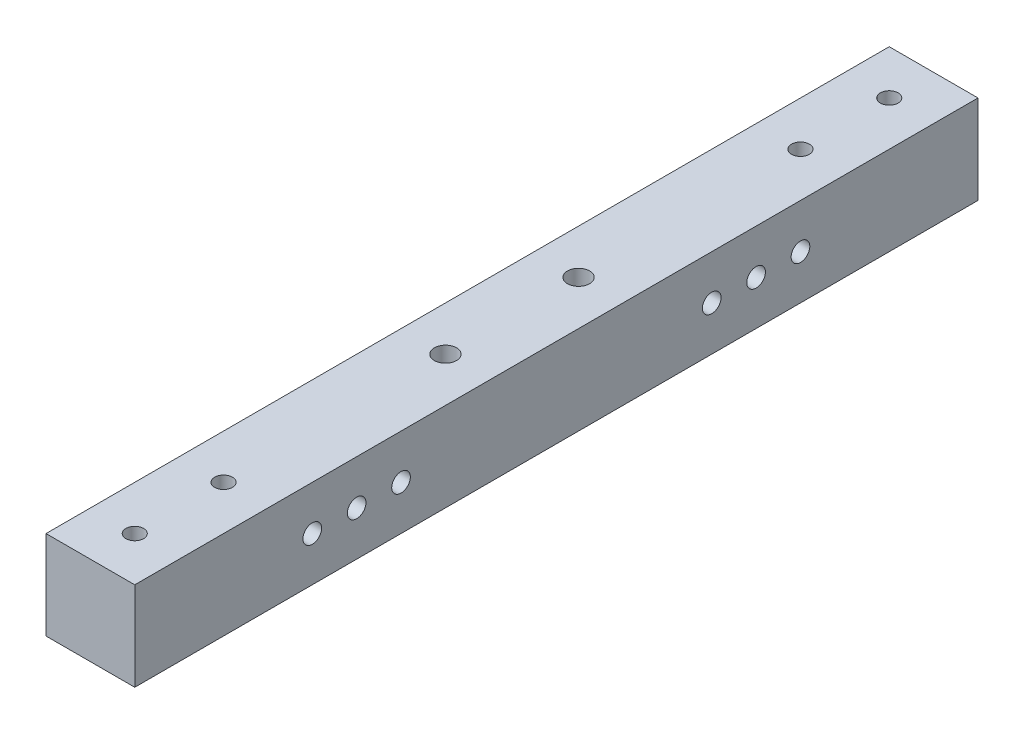
SolidWorks part; units mm, degrees
ref_plane "前视基准面" through (0, 0, 0) normal (0, 0, 1) x (1, 0, 0)
ref_plane "上视基准面" through (0, 0, 0) normal (0, 1, 0) x (1, 0, 0)
ref_plane "右视基准面" through (0, 0, 0) normal (1, 0, 0) x (0, 0, -1)
other "Configuration Table"
sketch "草图1" plane through (0, 0, 0) normal (0, 0, 1) x (1, 0, 0)
  line L1 (0, 0) -> (20, 0)
  line L2 (0, 0) -> (0, 20)
  line L3 (0, 20) -> (20, 20)
  line L4 (20, 0) -> (20, 20)
  dimension "D1" = 20
extrude "凸台-拉伸1" add sketch "草图1" along normal blind 190
sketch "草图2" plane through (0, 20, 0) normal (0, 1, 0) x (1, 0, 0)
  line L0 (10, -190) -> (10, 0) construction
  line L1 (20, -190) -> (0, -190) construction
  line L2 (20, 0) -> (0, 0) construction
  line L3 (0, -95) -> (20, -95) construction
  line L4 (0, -190) -> (0, 0) construction
  line L5 (20, -190) -> (20, 0) construction
  circle A0 centre (10, -180) radius 2
  circle A1 centre (10, -160) radius 2
  circle A2 centre (10, -110) radius 2.5
  circle A3 centre (10, -10) radius 2
  circle A4 centre (10, -30) radius 2
  circle A5 centre (10, -80) radius 2.5
  dimension "D6" = 50
  dimension "D7" = 50
  dimension "D8" = 20
  dimension "D1" = 10
  dimension "D2" = 20
  dimension "D3" = 30
extrude "切除-拉伸1" cut sketch "草图2" against normal through all both
sketch "草图3" plane through (20, 0, 0) normal (1, 0, 0) x (0, 0, -1)
  line L0 (-95, 20) -> (-95, 0) construction
  line L1 (-190, 20) -> (0, 20) construction
  line L2 (-190, 0) -> (0, 0) construction
  circle A0 centre (-140, 10) radius 2.1
  circle A1 centre (-130, 10) radius 2.1
  circle A2 centre (-150, 10) radius 2.1
  circle A3 centre (-60, 10) radius 2.1
  circle A4 centre (-50, 10) radius 2.1
  circle A5 centre (-40, 10) radius 2.1
  dimension "D1" = 45
  dimension "D3" = 4.2
  dimension "D6" = 4.2
  dimension "D2" = 10
  dimension "D5" = 10
  dimension "D7" = 10
  dimension "D4" = 2
extrude "切除-拉伸2" cut sketch "草图3" against normal through all
